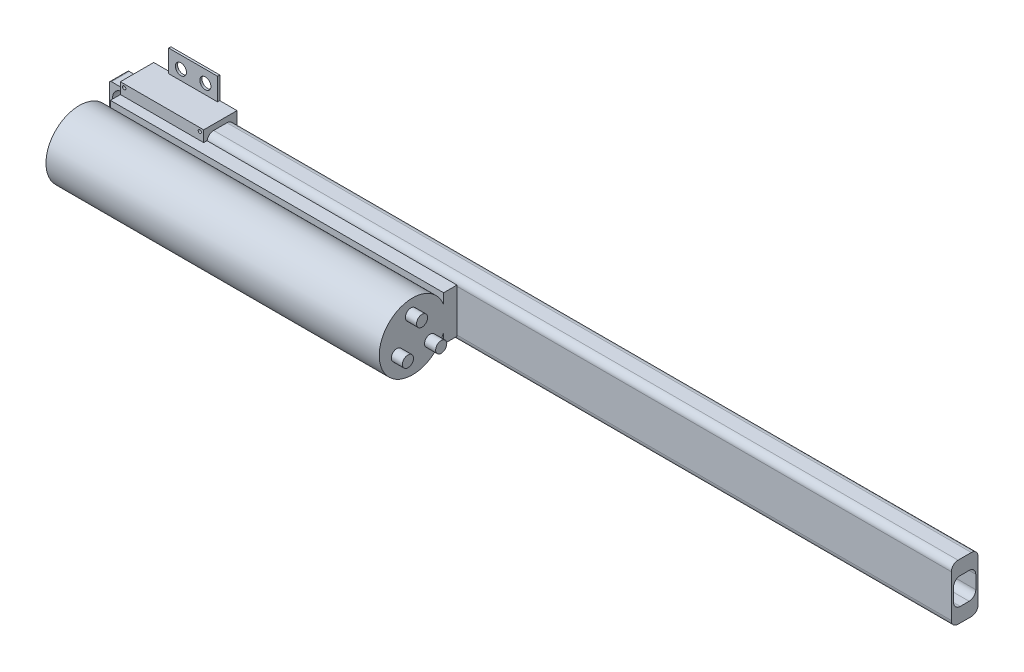
SolidWorks part; units mm, degrees
material "Acero inoxidable al cromo"
ref_plane "Front" through (0, 0, 0) normal (0, 0, 1) x (1, 0, 0)
ref_plane "Top" through (0, 0, 0) normal (0, 1, 0) x (1, 0, 0)
ref_plane "Right" through (0, 0, 0) normal (1, 0, 0) x (0, 0, -1)
sketch "Croquis1" plane through (0, 0, 0) normal (0, 0, 1) x (1, 0, 0)
  line L2 (-18.75, -15) -> (18.75, -15)
  line L3 (-18.75, -15) -> (-18.75, 15)
  line L4 (-18.75, 15) -> (18.75, 15)
  line L5 (18.75, -15) -> (18.75, 15)
  line L6 (-18.75, -15) -> (18.75, 15) construction
  line L7 (-18.75, 15) -> (18.75, -15) construction
  point P1 (0, 0)
  dimension "D1" = 37.5
  dimension "D2" = 30
extrude "Saliente-Extruir1" add sketch "Croquis1" along normal blind 15
sketch "Croquis2" plane through (0, 0, 0) normal (0, 0, 1) x (1, 0, 0)
  line L0 (-18.75, 15) -> (-18.75, -15) construction
  line L1 (-18.75, 6) -> (-29.75, 6)
  line L2 (-18.75, 6) -> (-18.75, -6)
  line L3 (-18.75, -6) -> (-29.75, -6)
  line L4 (-30.75, 5) -> (-30.75, -5)
  line L5 (0, 0) -> (-15.2309, 0) construction
  line L6 (-30.75, 0) -> (-18.75, 0) construction
  line L7 (18.75, 15) -> (-18.75, 15) construction
  line L12 (0, 0) -> (0, -15) construction
  line L13 (-18.75, -15) -> (18.75, -15) construction
  line L14 (11, 15) -> (-11, 15)
  line L15 (11, 15) -> (11, 25)
  line L16 (11, 25) -> (-11, 25)
  line L17 (-11, 15) -> (-11, 25)
  line L18 (11, -25) -> (-11, -25)
  line L19 (-11, -15) -> (-11, -25)
  line L20 (11, -15) -> (-11, -15)
  line L21 (11, -15) -> (11, -25)
  circle A0 centre (-24.75, 0) radius 4.5
  arc A1 (-29.75, -6) -> (-30.75, -5) centre (-29.75, -5) cw
  arc A2 (-29.75, 6) -> (-30.75, 5) centre (-29.75, 5) ccw
  circle A3 centre (5.5, 19.5) radius 2.5
  circle A4 centre (-5.5, 19.5) radius 2.5
  circle A5 centre (5.5, -19.5) radius 2.5
  circle A6 centre (-5.5, -19.5) radius 2.5
  point P16 (-30.75, -6)
  point P19 (-30.75, 6)
  dimension "D2" = 9
  dimension "D4" = 1
  dimension "D5" = 11
  dimension "D6" = 5
  dimension "D9" = 22
  dimension "D7" = 39
  dimension "D1" = 12
  dimension "D3" = 12
  dimension "D8" = 10
extrude "Saliente-Extruir2" add sketch "Croquis2" along normal blind 1
sketch "Croquis3" plane through (18.75, 0, 0) normal (1, 0, 0) x (0, 0, -1)
  line L0 (0, 0) -> (-15, 0) construction
  line L1 (-15, -15) -> (-15, 15) construction
  line L2 (0, -15) -> (0, 15) construction
  line L3 (-10.5, -12.5) -> (-4.5, -12.5)
  line L4 (-13.5, -9.5) -> (-13.5, 9.5)
  line L5 (-10.5, 12.5) -> (-4.5, 12.5)
  line L6 (-1.5, -9.5) -> (-1.5, 9.5)
  line L7 (-13.5, -12.5) -> (-1.5, 12.5) construction
  line L8 (-13.5, 12.5) -> (-1.5, -12.5) construction
  arc A0 (-10.5, -12.5) -> (-13.5, -9.5) centre (-10.5, -9.5) cw
  arc A1 (-4.5, -12.5) -> (-1.5, -9.5) centre (-4.5, -9.5) ccw
  arc A2 (-4.5, 12.5) -> (-1.5, 9.5) centre (-4.5, 9.5) cw
  arc A3 (-13.5, 9.5) -> (-10.5, 12.5) centre (-10.5, 9.5) cw
  point P5 (-7.5, 0)
  dimension "D3" = 3
  dimension "D1" = 1.5
  dimension "D2" = 25
sketch "Croquis4" plane through (0, 0, 15) normal (0, 0, 1) x (1, 0, 0)
  line L0 (-24.75, 0) -> (62.75, 0) construction
  dimension "D1" = 87.5
extrude "Saliente-Extruir3" add sketch "Croquis3" along normal blind 35
ref_plane "Plano1" through (0, 0, 7.5) normal (0, 0, 1) x (1, 0, 0)
sketch "Croquis5" plane through (0, 0, 7.5) normal (0, 0, 1) x (1, 0, 0)
  line L14 (-24.75, 0) -> (62.75, 0) construction
  line L15 (53.75, 6) -> (71.75, 6)
  line L16 (53.75, 9.5) -> (53.75, -9.5) construction
  line L17 (71.75, 6) -> (71.75, -6)
  line L18 (71.75, -6) -> (53.75, -6)
  line L19 (53.75, -6) -> (53.75, 6)
  circle A1 centre (62.75, 0) radius 4.5
  dimension "D1" = 12
  dimension "D2" = 6
  dimension "9" = 9
  dimension "D3" = 18
extrude "Saliente-Extruir4" add sketch "Croquis5" along normal mid plane 10
sketch "Croquis6" plane through (71.75, 0, 0) normal (1, 0, 0) x (0, 0, -1)
  line L0 (-11.5, 6) -> (-11.5, -6)
  line L1 (-12.5, 6) -> (-2.5, 6) construction
  line L2 (-12.5, -6) -> (-2.5, -6) construction
  line L3 (-3.5, 6) -> (-3.5, -6)
  line L4 (-12.5, 6) -> (-2.5, 6) construction
  line L5 (-12.5, -6) -> (-2.5, -6) construction
  line L6 (-12.5, -6) -> (-12.5, 6) construction
  line L7 (-2.5, -6) -> (-2.5, 6) construction
  line L8 (-3.5, -6) -> (-2.5, -6)
  line L9 (-11.5, 6) -> (-12.5, 6)
  line L12 (-2.5, -6) -> (-2.5, 6)
  line L13 (-2.5, 6) -> (-12.5, 6)
  line L14 (-12.5, 6) -> (-12.5, -6)
  line L15 (-12.5, -6) -> (-2.5, -6)
  line L16 (-2.5, -6) -> (-2.5, 6)
  line L17 (-2.5, 6) -> (-3.5, 6)
  line L18 (-12.5, 6) -> (-12.5, -6)
  line L19 (-12.5, -6) -> (-11.5, -6)
  dimension "D1" = 1
  dimension "D2" = 1
  dimension "D3" = 0
extrude "Cortar-Extruir2" cut sketch "Croquis6" against normal blind 14
fillet "Redondeo1" radius 3 2 edges at (71.75, -6, 7.5) (71.75, 6, 7.5)
fillet "Redondeo2" radius 3 4 edges at (55.75, -6, 12.5) (55.75, -6, 2.5) (55.75, 6, 2.5) (55.75, 6, 12.5)
sketch "Croquis7" plane through (0, 0, 15) normal (0, 0, 1) x (1, 0, 0)
  line L1 (53.75, 11.9051) -> (112.4881, 11.9051)
  line L2 (53.75, 11.9051) -> (53.75, -24.3061)
  line L3 (53.75, -24.3061) -> (112.4881, -24.3061)
  line L4 (112.4881, 11.9051) -> (112.4881, -24.3061)
  line L6 (53.75, 9.5) -> (53.75, -9.5) construction
extrude "Cortar-Extruir4" cut sketch "Croquis7" against normal through all
sketch "Croquis8" plane through (53.75, 0, 0) normal (1, 0, 0) x (0, 0, -1)
  line L0 (-13.5, 0) -> (-1.5, 0) construction
  line L1 (-13.5, 9.5) -> (-13.5, -9.5) construction
  line L2 (-1.5, -9.5) -> (-1.5, 9.5) construction
  line L4 (-9.5, -6) -> (-5.5, -6)
  line L5 (-12.5, -3) -> (-12.5, 3)
  line L6 (-9.5, 6) -> (-5.5, 6)
  line L7 (-2.5, -3) -> (-2.5, 3)
  line L8 (-12.5, -6) -> (-2.5, 6) construction
  line L9 (-12.5, 6) -> (-2.5, -6) construction
  arc A0 (-5.5, -6) -> (-2.5, -3) centre (-5.5, -3) ccw
  arc A1 (-9.5, -6) -> (-12.5, -3) centre (-9.5, -3) cw
  arc A2 (-12.5, 3) -> (-9.5, 6) centre (-9.5, 3) cw
  arc A3 (-5.5, 6) -> (-2.5, 3) centre (-5.5, 3) cw
  point P6 (-7.5, 0)
  dimension "D3" = 3
  dimension "D1" = 10
  dimension "D2" = 12
extrude "Cortar-Extruir5" cut sketch "Croquis8" against normal blind 30
sketch "Croquis9" plane through (0, 0, 15) normal (0, 0, 1) x (1, 0, 0)
  line L1 (-17, -13.5) -> (17, -13.5) construction
  line L2 (-17, -13.5) -> (-17, 13.5) construction
  line L3 (-17, 13.5) -> (17, 13.5) construction
  line L4 (17, -13.5) -> (17, 13.5) construction
  line L5 (-17, -13.5) -> (17, 13.5) construction
  line L6 (-17, 13.5) -> (17, -13.5) construction
  circle A0 centre (-17, 13.5) radius 0.75
  circle A1 centre (17, 13.5) radius 0.75
  circle A2 centre (17, -13.5) radius 0.75
  circle A3 centre (-17, -13.5) radius 0.75
  point P8 (0, 0)
  dimension "D1" = 1.5
  dimension "D2" = 34
  dimension "D3" = 27
extrude "Cortar-Extruir6" cut sketch "Croquis9" against normal blind 2
sketch "Croquis10" plane through (0, 0, 1) normal (0, 0, 1) x (1, 0, 0)
  line L4 (-18.75, -6) -> (-18.75, 6)
  line L5 (-18.75, 6) -> (-29.75, 6)
  line L6 (-30.75, 5) -> (-30.75, -5)
  line L7 (-29.75, -6) -> (-18.75, -6)
  line L8 (-18.75, -6) -> (-18.75, 6)
  line L9 (-18.75, 6) -> (-29.75, 6)
  line L10 (-30.75, 5) -> (-30.75, -5)
  line L11 (-29.75, -6) -> (-18.75, -6)
  circle A0 centre (-24.75, 0) radius 4.5 construction
  circle A1 centre (-24.75, 0) radius 4.5
  arc A2 (-29.75, 6) -> (-30.75, 5) centre (-29.75, 5) ccw
  arc A3 (-30.75, -5) -> (-29.75, -6) centre (-29.75, -5) ccw
  arc A4 (-29.75, 6) -> (-30.75, 5) centre (-29.75, 5) ccw
  arc A5 (-30.75, -5) -> (-29.75, -6) centre (-29.75, -5) ccw
  dimension "D1" = 0
extrude "Saliente-Extruir5" add sketch "Croquis10" along normal blind 7
sketch "Croquis11" plane through (53.75, 0, 0) normal (1, 0, 0) x (0, 0, -1)
  line L0 (-5.5, 6) -> (-9.5, 6) construction
  line L1 (-5.5, 6) -> (-9.5, 6)
  line L2 (-12.5, 3) -> (-12.5, -3) construction
  line L3 (-9.5, -6) -> (-5.5, -6) construction
  line L4 (-13.5, 9.5) -> (-13.5, -9.5)
  line L5 (-10.5, -12.5) -> (-4.5, -12.5)
  line L6 (-1.5, -9.5) -> (-1.5, 9.5)
  line L7 (-4.5, 12.5) -> (-10.5, 12.5)
  line L8 (-13.5, 9.5) -> (-13.5, -9.5)
  line L9 (-10.5, -12.5) -> (-4.5, -12.5)
  line L10 (-1.5, -9.5) -> (-1.5, 9.5)
  line L11 (-4.5, 12.5) -> (-10.5, 12.5)
  line L12 (-2.5, -3) -> (-2.5, 3) construction
  line L13 (-12.5, 3) -> (-12.5, -3)
  line L14 (-9.5, -6) -> (-5.5, -6)
  line L15 (-2.5, -3) -> (-2.5, 3)
  arc A0 (-9.5, 6) -> (-12.5, 3) centre (-9.5, 3) ccw construction
  arc A1 (-12.5, -3) -> (-9.5, -6) centre (-9.5, -3) ccw construction
  arc A2 (-5.5, -6) -> (-2.5, -3) centre (-5.5, -3) ccw construction
  arc A3 (-2.5, 3) -> (-5.5, 6) centre (-5.5, 3) ccw construction
  arc A4 (-10.5, 12.5) -> (-13.5, 9.5) centre (-10.5, 9.5) ccw
  arc A5 (-13.5, -9.5) -> (-10.5, -12.5) centre (-10.5, -9.5) ccw
  arc A6 (-4.5, -12.5) -> (-1.5, -9.5) centre (-4.5, -9.5) ccw
  arc A7 (-1.5, 9.5) -> (-4.5, 12.5) centre (-4.5, 9.5) ccw
  arc A8 (-10.5, 12.5) -> (-13.5, 9.5) centre (-10.5, 9.5) ccw
  arc A9 (-13.5, -9.5) -> (-10.5, -12.5) centre (-10.5, -9.5) ccw
  arc A10 (-4.5, -12.5) -> (-1.5, -9.5) centre (-4.5, -9.5) ccw
  arc A11 (-1.5, 9.5) -> (-4.5, 12.5) centre (-4.5, 9.5) ccw
  arc A12 (-9.5, 6) -> (-12.5, 3) centre (-9.5, 3) ccw
  arc A13 (-12.5, -3) -> (-9.5, -6) centre (-9.5, -3) ccw
  arc A14 (-5.5, -6) -> (-2.5, -3) centre (-5.5, -3) ccw
  arc A15 (-2.5, 3) -> (-5.5, 6) centre (-5.5, 3) ccw
  dimension "D1" = 0
extrude "Saliente-Extruir6" add sketch "Croquis11" along normal blind 300
sketch "Croquis12" plane through (-18.75, 0, 0) normal (-1, 0, 0) x (0, 0, 1)
  line L0 (15, 15) -> (15, -15) construction
  line L1 (33.5, 0) -> (0, 0) construction
  circle A0 centre (33.5, 0) radius 15
  dimension "D1" = 18.5
  dimension "35" = 30
extrude "Saliente-Extruir7" add sketch "Croquis12" against normal blind 150 separate body
sketch "Croquis13" plane through (131.25, 0, 0) normal (1, 0, 0) x (0, 0, -1)
  line L0 (-13.5, 9.5) -> (-13.5, -9.5) construction
  line L1 (-19.5, 10) -> (-13.5, 10)
  line L2 (-19.5, 10) -> (-19.5, -10)
  line L3 (-19.5, -10) -> (-13.5, -10)
  line L4 (-13.5, 10) -> (-13.5, -10)
  line L5 (0, 0) -> (-38.8037, 0) construction
  dimension "D1" = 6
  dimension "D2" = 20
extrude "Saliente-Extruir8" add sketch "Croquis13" against normal blind 150
sketch "Croquis14" plane through (131.25, 0, 0) normal (1, 0, 0) x (0, 0, -1)
  circle A0 centre (-34.2241, 8.9523) radius 2.5
  circle A1 centre (-40.5562, -3.7119) radius 2.5
  circle A2 centre (-25.5994, -5.5679) radius 2.5
  dimension "D1" = 5
extrude "Saliente-Extruir9" add sketch "Croquis14" along normal blind 5
